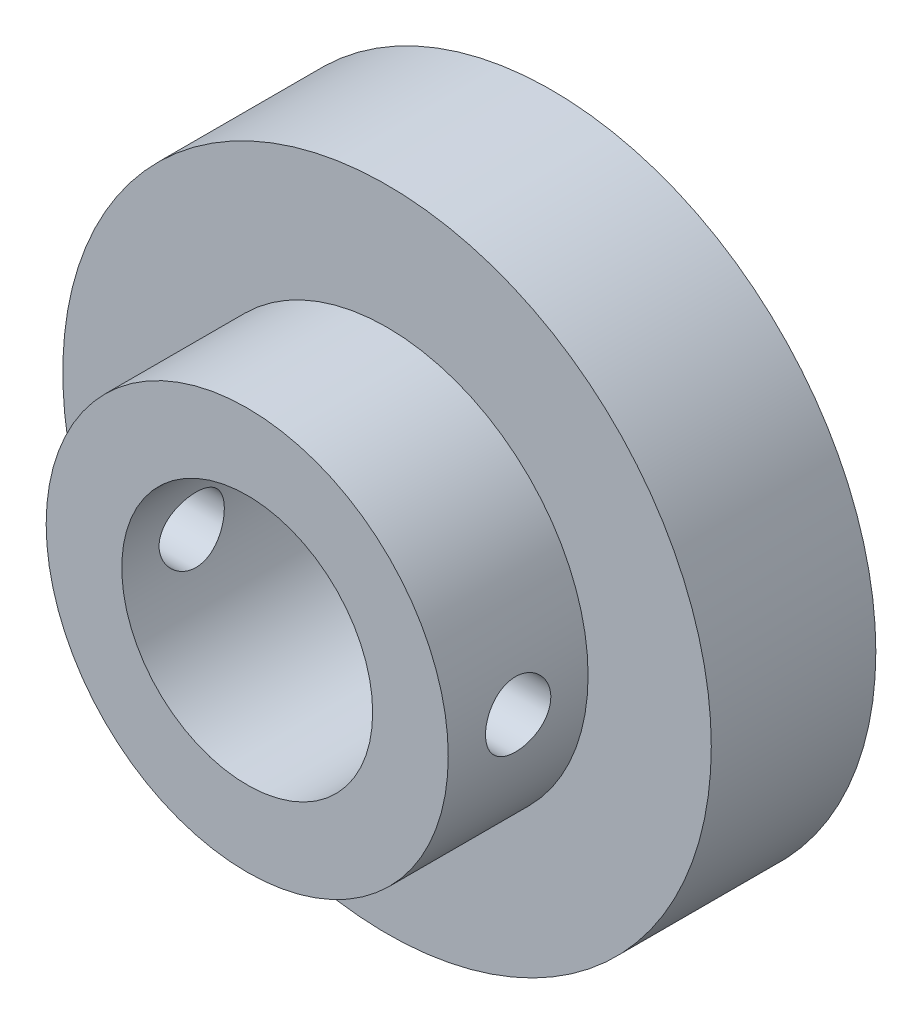
SolidWorks part; units mm, degrees
ref_plane "Front Plane" through (0, 0, 0) normal (1, 0, 0) x (0, 1, 0)
ref_plane "Top Plane" through (0, 0, 0) normal (0, 0, 1) x (0, 1, 0)
ref_plane "Right Plane" through (0, 0, 0) normal (0, 1, 0) x (-1, 0, 0)
sketch "Sketch1" plane through (0, 0, 0) normal (0, 0, 1) x (0, 1, 0)
  circle A0 centre (0, 0) radius 20.87
  dimension "D1" = 41.74
extrude "Boss-Extrude1" add sketch "Sketch1" along normal blind 10.59
sketch "Sketch2" plane through (0, 0, 10.59) normal (0, 0, 1) x (1, 0, 0)
  circle A0 centre (0, 0) radius 12.94
  dimension "D1" = 25.88
extrude "Boss-Extrude2" add sketch "Sketch2" along normal blind 9
sketch "Sketch3" plane through (0, 0, 19.59) normal (0, 0, 1) x (1, 0, 0)
  circle A0 centre (0, 0) radius 8.075
  dimension "D1" = 16.15
extrude "Cut-Extrude1" cut sketch "Sketch3" against normal through all both and the other way through all
sketch "Sketch4" plane through (0, 0, 0) normal (1, 0, 0) x (0, 1, 0)
  line L0 (0, 19.59) -> (0, 10.59) construction
  line L1 (12.94, 19.59) -> (-12.94, 19.59) construction
  line L2 (20.87, 10.59) -> (-20.87, 10.59) construction
  circle A0 centre (0, 15.09) radius 2.1
  dimension "D1" = 4.2
extrude "Cut-Extrude2" cut sketch "Sketch4" against normal through all both and the other way through all
